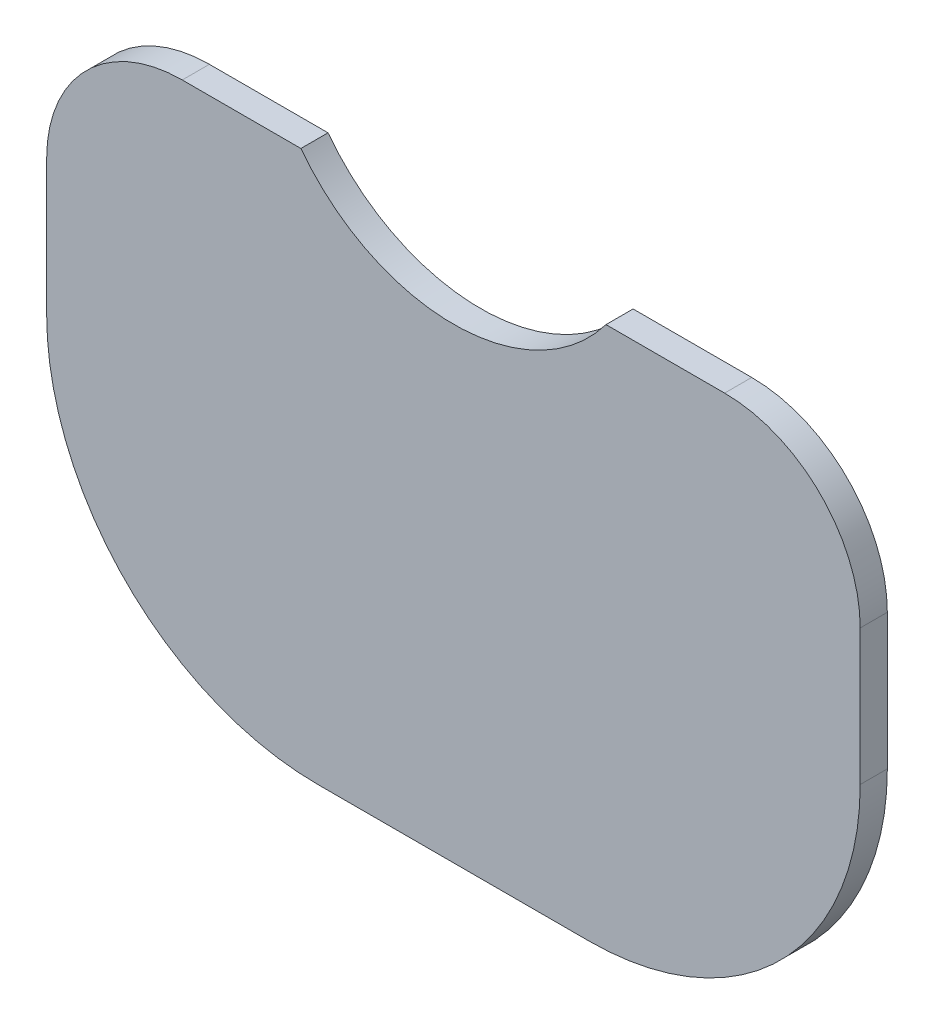
SolidWorks part; units mm, degrees
ref_plane "前视基准面" through (0, 0, 0) normal (0, 0, 1) x (1, 0, 0)
ref_plane "上视基准面" through (0, 0, 0) normal (0, 1, 0) x (1, 0, 0)
ref_plane "右视基准面" through (0, 0, 0) normal (1, 0, 0) x (0, 0, -1)
other "Configuration Table"
sketch "草图1" plane through (0, 0, 0) normal (0, 0, 1) x (1, 0, 0)
  line L1 (10, -20) -> (-10, -20)
  line L2 (30, 0) -> (30, 10)
  line L3 (20, 20) -> (-20, 20)
  line L4 (-30, 0) -> (-30, 10)
  line L5 (30, -20) -> (-30, 20) construction
  line L6 (30, 20) -> (-30, -20) construction
  arc A0 (-30, 10) -> (-20, 20) centre (-20, 10) cw
  arc A1 (30, 10) -> (20, 20) centre (20, 10) ccw
  circle A4 centre (0, 28.5) radius 14.1
  arc A5 (30, 0) -> (10, -20) centre (10, 0) cw
  arc A6 (-10, -20) -> (-30, 0) centre (-10, 0) cw
  point P0 (0, 0)
  dimension "D3" = 10
  dimension "D4" = 28.2
  dimension "D6" = 20
  dimension "D1" = 60
  dimension "D2" = 40
  dimension "D5" = 8.5
extrude "凸台-拉伸1" add sketch "草图1" along normal blind 2 contours A6 L1 A5 L2 A1 L3 A4 A0 L4
sketch "草图3" plane through (0, 0, 0) normal (0, 0, 1) x (1, 0, 0)
  line L0 (20, 20) -> (11.2499, 20) construction
  line L1 (0, 14.4) -> (0, -20) construction
  line L2 (10, -20) -> (-10, -20) construction
  circle A0 centre (-12.5, 0) radius 7.5
  circle A1 centre (12.5, 0) radius 7.5
  arc A2 (-11.2499, 20) -> (11.2499, 20) centre (0, 28.5) ccw construction
  dimension "D1" = 15
  dimension "D2" = 15
  dimension "D3" = 20
  dimension "D4" = 12.5
  dimension "D5" = 12.5
extrude "凸台-拉伸2" add sketch "草图3" against normal blind 6.5
